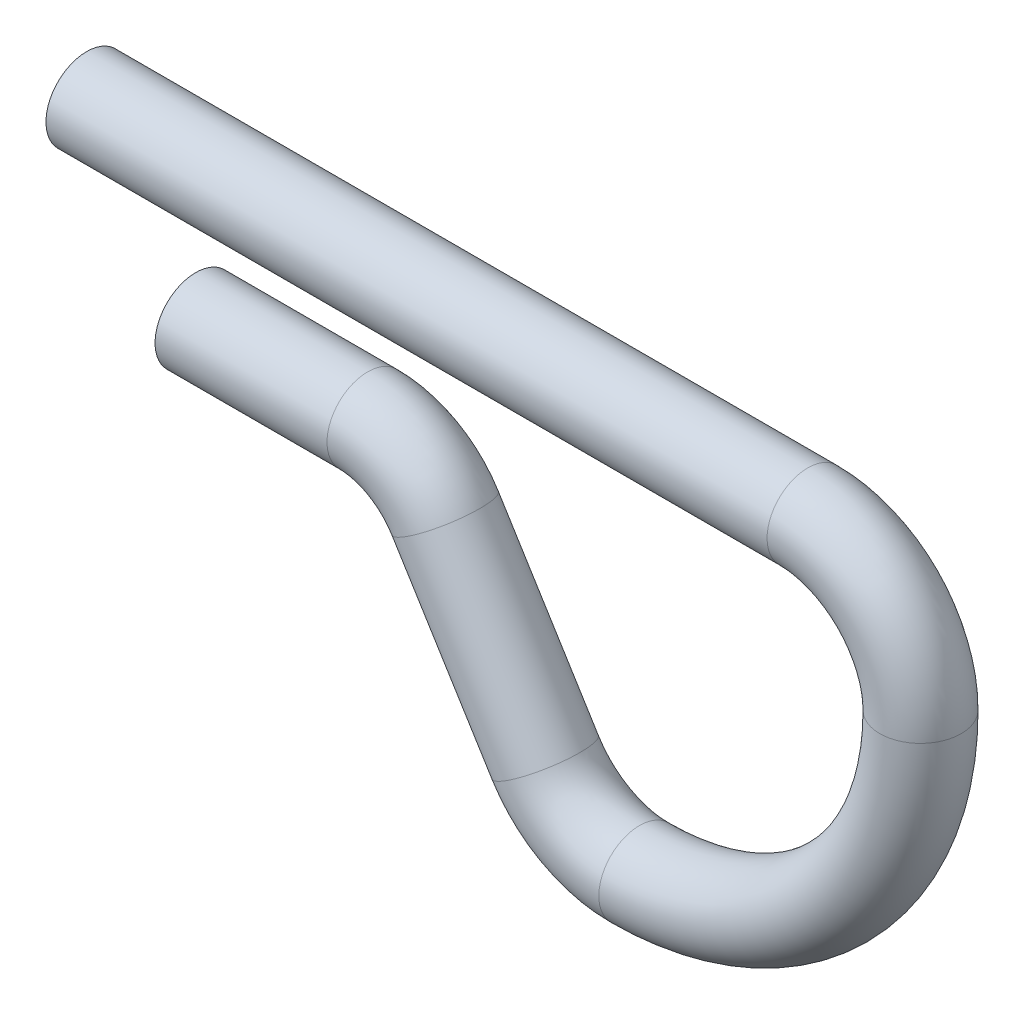
SolidWorks part; units mm, degrees
ref_plane "Front Plane" through (0, 0, 0) normal (0, 0, 1) x (1, 0, 0)
ref_plane "Top Plane" through (0, 0, 0) normal (0, 1, 0) x (1, 0, 0)
ref_plane "Right Plane" through (0, 0, 0) normal (1, 0, 0) x (0, 0, -1)
sketch "Sketch2" plane through (0, 0, 0) normal (0, 0, 1) x (1, 0, 0)
  line L0 (-14.986, 18.796) -> (84.074, 18.796)
  line L1 (48.006, -28.0942) -> (34.2679, -5.9269)
  line L2 (23.622, 0) -> (0, 0)
  arc A0 (84.074, 18.796) -> (99.568, 3.302) centre (84.074, 3.302) cw
  arc A1 (99.568, 3.302) -> (60.96, -35.306) centre (60.96, 3.302) cw
  arc A2 (60.96, -35.306) -> (48.006, -28.0942) centre (60.96, -20.066) cw
  arc A3 (34.2679, -5.9269) -> (23.622, 0) centre (23.622, -12.5246) ccw
  dimension "D2" = 15.494
  dimension "D4" = 38.608
  dimension "D1" = 99.06
  dimension "D3" = 23.368
  dimension "D5" = 18.796
  dimension "D6" = 36.068
  dimension "D7" = 84.074
  dimension "D8" = 60.452
ref_plane "Plane1" through (-14.986, 0, 0) normal (1, 0, 0) x (0, 0, -1)
sketch "Sketch3" plane through (-14.986, 0, 0) normal (1, 0, 0) x (0, 0, -1)
  circle A0 centre (0, 18.796) radius 5.588
  dimension "D1" = 11.176
sweep "Sweep1" add profiles "Sketch3" path "Sketch2"
